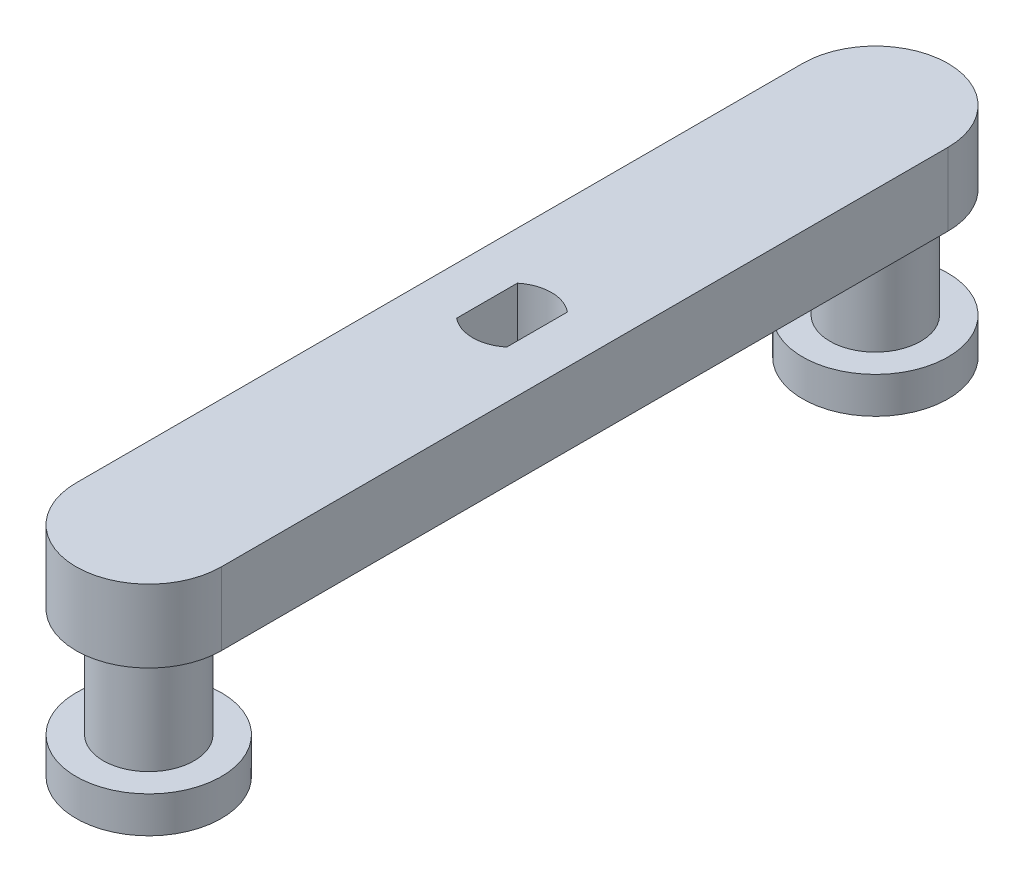
SolidWorks part; units mm, degrees
ref_plane "Front Plane" through (0, 0, 0) normal (0, 0, 1) x (1, 0, 0)
ref_plane "Top Plane" through (0, 0, 0) normal (0, 1, 0) x (1, 0, 0)
ref_plane "Right Plane" through (0, 0, 0) normal (1, 0, 0) x (0, 0, -1)
sketch "Sketch1" plane through (0, 0, 0) normal (0, 1, 0) x (1, 0, 0)
  line L0 (0, 0) -> (0, 25.4)
  line L1 (0, 0) -> (0, -25.4)
  line L4 (-5.08, 25.4) -> (-5.08, -25.4)
  line L5 (5.08, -25.4) -> (5.08, 25.4)
  arc A0 (5.08, 25.4) -> (-5.08, 25.4) centre (0, 25.4) ccw
  arc A1 (-5.08, -25.4) -> (5.08, -25.4) centre (0, -25.4) ccw
sketch "Sketch2" plane through (0, 0, 0) normal (0, 1, 0) x (1, 0, 0)
  line L0 (-5.08, 25.4) -> (-5.08, -25.4)
  line L1 (5.08, -25.4) -> (5.08, 25.4)
  arc A0 (5.08, 25.4) -> (-5.08, 25.4) centre (0, 25.4) ccw
  arc A1 (-5.08, -25.4) -> (5.08, -25.4) centre (0, -25.4) ccw
extrude "Boss-Extrude1" add sketch "Sketch2" along normal blind 5.08
sketch "Sketch3" plane through (0, 0, 0) normal (0, -1, 0) x (-1, 0, 0)
  circle A0 centre (0, -25.4) radius 3.175
  circle A1 centre (0, 25.4) radius 3.175
extrude "Boss-Extrude2" add sketch "Sketch3" along normal blind 7.62
sketch "Sketch5" plane through (0, -7.62, 0) normal (0, -1, 0) x (1, 0, 0)
  circle A0 centre (0, 25.4) radius 5.08
sketch "Sketch6" plane through (0, -7.62, 0) normal (0, -1, 0) x (1, 0, 0)
  circle A0 centre (0, 25.4) radius 5.08
extrude "Boss-Extrude3" add sketch "Sketch6" along normal blind 2.54
sketch "Sketch7" plane through (0, -7.62, 0) normal (0, -1, 0) x (1, 0, 0)
  circle A0 centre (0, -25.4) radius 5.08
sketch "Sketch8" plane through (0, -7.62, 0) normal (0, -1, 0) x (1, 0, 0)
  circle A0 centre (0, -25.4) radius 5.08
extrude "Boss-Extrude4" add sketch "Sketch8" along normal blind 2.54
sketch "Sketch9" plane through (0, 5.08, 0) normal (0, 1, 0) x (1, 0, 0)
  line L0 (0, 0) -> (-1.75, 0)
  line L1 (-1.75, 0) -> (0, 0)
  line L2 (0, 0) -> (1.75, 0)
  line L3 (-1.75, 0) -> (-1.75, 2.1213)
  line L4 (-1.75, 2.1213) -> (-1.75, -2.1213)
  line L5 (1.75, 0) -> (1.75, 2.1213)
  line L6 (1.75, 2.1213) -> (1.75, -2.1213)
  arc A0 (1.75, 2.1213) -> (-1.75, 2.1213) centre (0, 0) ccw
  arc A1 (-1.75, -2.1213) -> (1.75, -2.1213) centre (0, 0) ccw
sketch "Sketch10" plane through (0, 5.08, 0) normal (0, 1, 0) x (1, 0, 0)
  line L0 (-1.75, 2.1213) -> (-1.75, -2.1213)
  line L1 (1.75, 2.1213) -> (1.75, -2.1213)
  arc A0 (1.75, 2.1213) -> (-1.75, 2.1213) centre (0, 0) ccw
  arc A1 (-1.75, -2.1213) -> (1.75, -2.1213) centre (0, 0) ccw
extrude "Cut-Extrude1" cut sketch "Sketch10" against normal up to next
